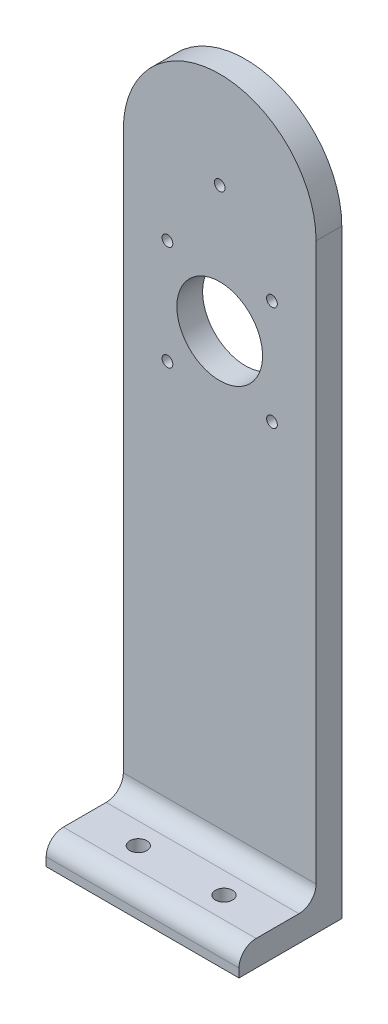
SolidWorks part; units mm, degrees
material "ABS"
ref_plane "Front Plane" through (0, 0, 0) normal (0, 0, 1) x (1, 0, 0)
ref_plane "Top Plane" through (0, 0, 0) normal (0, 1, 0) x (1, 0, 0)
ref_plane "Right Plane" through (0, 0, 0) normal (1, 0, 0) x (0, 0, -1)
sketch "Sketch1" plane through (0, 0, 0) normal (0, 0, 1) x (1, 0, 0)
  line L0 (-28.575, 0) -> (-28.575, -177.8)
  line L1 (-28.575, -177.8) -> (28.575, -177.8)
  line L2 (28.575, -177.8) -> (28.575, 0)
  arc A0 (-28.575, 0) -> (28.575, 0) centre (0, 0) cw
  dimension "D1" = 28.575
  dimension "D2" = 177.8
extrude "Boss-Extrude1" add sketch "Sketch1" along normal blind 7.62
sketch "Sketch2" plane through (-28.575, 0, 0) normal (-1, 0, 0) x (0, 0, 1)
  line L1 (0, -177.8) -> (30.48, -177.8)
  line L2 (0, -177.8) -> (0, -170.18)
  line L3 (0, -170.18) -> (25.4, -170.18)
  line L4 (30.48, -177.8) -> (30.48, -175.26)
  arc A0 (25.4, -170.18) -> (30.48, -175.26) centre (25.4, -175.26) cw
  point P7 (30.48, -170.18)
  dimension "D3" = 5.08
  dimension "D1" = 7.62
  dimension "D2" = 30.48
extrude "Boss-Extrude2" add sketch "Sketch2" against normal through all
fillet "Fillet1" radius 5.08 1 edges at (0, -170.18, 7.62)
sketch "Sketch3" plane through (0, -170.18, 0) normal (0, 1, 0) x (1, 0, 0)
  line L0 (-28.575, -25.4) -> (-28.575, -12.7) construction
  circle A0 centre (12.7, -19.05) radius 2.54
  circle A1 centre (-12.7, -19.05) radius 2.54
  dimension "D1" = 5.08
  dimension "D2" = 5.08
  dimension "D3" = 25.4
  dimension "D4" = 15.875
extrude "Cut-Extrude1" cut sketch "Sketch3" against normal through all
sketch "Sketch4" plane through (0, 0, 0) normal (0, 0, -1) x (-1, 0, 0)
  line L0 (-28.575, -177.8) -> (-28.575, 0) construction
  line L1 (28.575, 0) -> (28.575, -177.8) construction
  circle A0 centre (0, 0) radius 1.5875
  arc A1 (28.575, 0) -> (-28.575, 0) centre (0, 0) ccw construction
  point P9 (0, 28.575)
  dimension "D1" = 3.175
  dimension "D2" = 28.575
  dimension "D3" = 28.575
  dimension "D4" = 0
  dimension "D5" = 28.575
extrude "Cut-Extrude2" cut sketch "Sketch4" against normal through all
sketch "Sketch5" plane through (0, 0, 0) normal (0, 0, -1) x (-1, 0, 0)
  circle A0 centre (0, -37.465) radius 12.7
  arc A2 (28.575, 0) -> (-28.575, 0) centre (0, 0) ccw construction
  point P5 (0, 28.575)
  dimension "D1" = 66.04
  dimension "D2" = 25.4
extrude "Cut-Extrude3" cut sketch "Sketch5" against normal through all
sketch "Sketch7" plane through (0, 0, 0) normal (0, 0, -1) x (-1, 0, 0)
  circle A0 centre (-15.494, -21.971) radius 1.5875
  circle A1 centre (15.494, -21.971) radius 1.5875
  circle A2 centre (15.494, -52.959) radius 1.5875
  circle A3 centre (-15.494, -52.959) radius 1.5875
  point P0 (0, -37.465)
  dimension "D3" = 3.175
  dimension "D4" = 3.175
  dimension "D5" = 3.175
  dimension "D6" = 3.175
  dimension "D1" = 30.988
  dimension "D2" = 30.988
extrude "Cut-Extrude4" cut sketch "Sketch7" against normal through all
